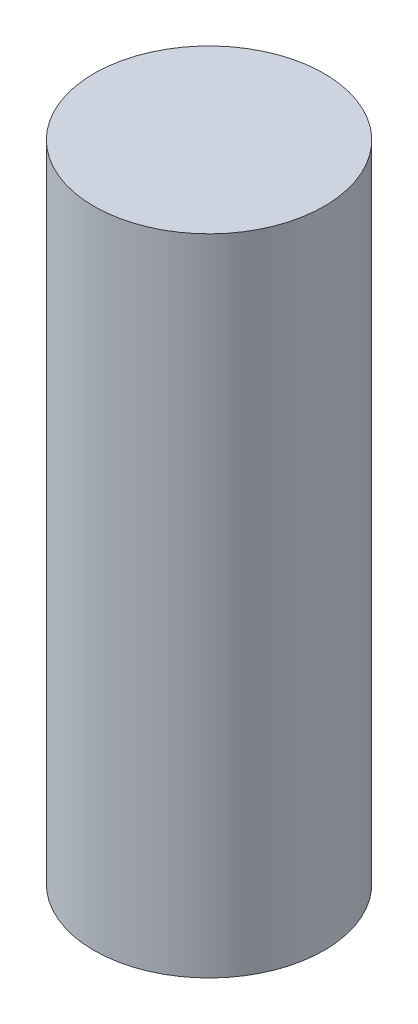
SolidWorks part; units mm, degrees
material "Silicon"
ref_plane "Front Plane" through (0, 0, 0) normal (0, 0, 1) x (1, 0, 0)
ref_plane "Top Plane" through (0, 0, 0) normal (0, 1, 0) x (1, 0, 0)
ref_plane "Right Plane" through (0, 0, 0) normal (1, 0, 0) x (0, 0, -1)
sketch "Drogue Chute Profile" plane through (0, 0, 0) normal (0, 1, 0) x (1, 0, 0)
  circle A0 centre (0, 0) radius 31.75
  dimension "D1" = 63.5
extrude "Drogue Chute Body" add sketch "Drogue Chute Profile" along normal blind 177.8
equation "\"Packed Diameter\"= 2.5"
equation "\"Packed Length\"= 7"
equation "\"D1@Drogue Chute Profile\"=\"Packed Diameter\""
equation "\"D1@Drogue Chute Body\"=\"Packed Length\""
